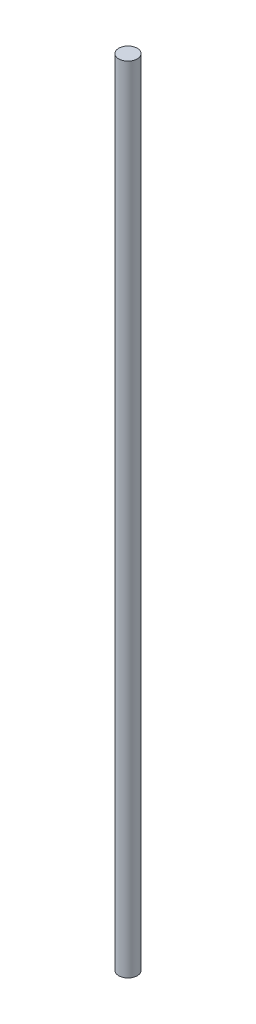
SolidWorks part; units mm, degrees
ref_plane "Ön Düzlem" through (0, 0, 0) normal (0, 0, 1) x (1, 0, 0)
ref_plane "Üst Düzlem" through (0, 0, 0) normal (0, 1, 0) x (1, 0, 0)
ref_plane "Sağ Düzlem" through (0, 0, 0) normal (1, 0, 0) x (0, 0, -1)
sketch "Sketch1" plane through (0, 0, 0) normal (0, 1, 0) x (1, 0, 0)
  circle A0 centre (0, 0) radius 3.5
  dimension "D1" = 7
extrude "Boss-Extrude1" add sketch "Sketch1" along normal blind 300
sketch "Sketch2" plane through (0, 0, 0) normal (0, -1, 0) x (1, 0, 0)
  circle A0 centre (0, 0) radius 2.5
  dimension "D1" = 5
extrude "Cut-Extrude1" cut sketch "Sketch2" against normal blind 11
